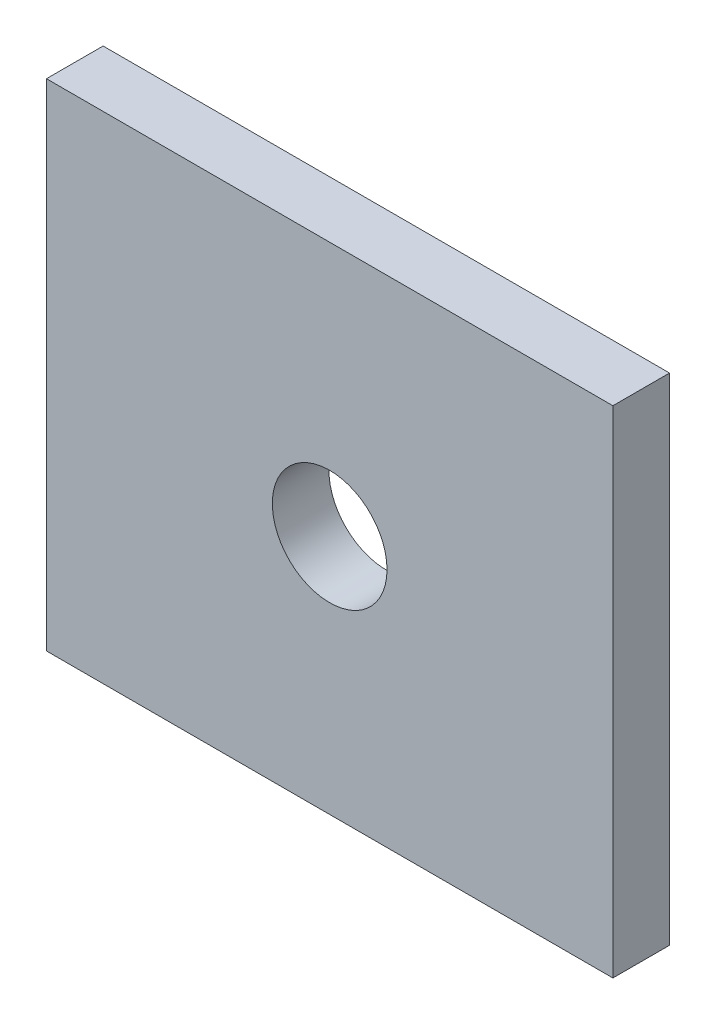
SolidWorks part; units mm, degrees
ref_plane "Front Plane" through (0, 0, 0) normal (0, 0, 1) x (1, 0, 0)
ref_plane "Top Plane" through (0, 0, 0) normal (0, 1, 0) x (1, 0, 0)
ref_plane "Right Plane" through (0, 0, 0) normal (1, 0, 0) x (0, 0, -1)
sketch "Sketch1" plane through (0, 0, 0) normal (0, 0, 1) x (1, 0, 0)
  line L1 (0, 0) -> (40, 0)
  line L2 (0, 0) -> (0, 35)
  line L3 (0, 35) -> (40, 35)
  line L4 (40, 0) -> (40, 35)
  dimension "D1" = 40
  dimension "D2" = 35
extrude "Profile" add sketch "Sketch1" along normal blind 4
sketch "Sketch2" plane through (0, 0, 0) normal (0, 0, 1) x (1, 0, 0)
  circle A0 centre (20, 17) radius 4.05
  dimension "D1" = 8.1
extrude "Fastener_clearance" cut sketch "Sketch2" against normal through all and the other way through all
equation "\"Profile_Depth\"= 4mm"
equation "\"D1@Profile\" = \"Profile_Depth\""
equation "\"Profile_Sketch_1\"= 40mm"
equation "\"D1@Sketch1\" = \"Profile_Sketch_1\""
equation "\"Profile_Sketch_2\"= 35mm"
equation "\"D2@Sketch1\" = \"Profile_Sketch_2\""
equation "\"EnvelopeWidth\"= 40mm"
equation "\"EnvelopeHeight\"= 35mm"
